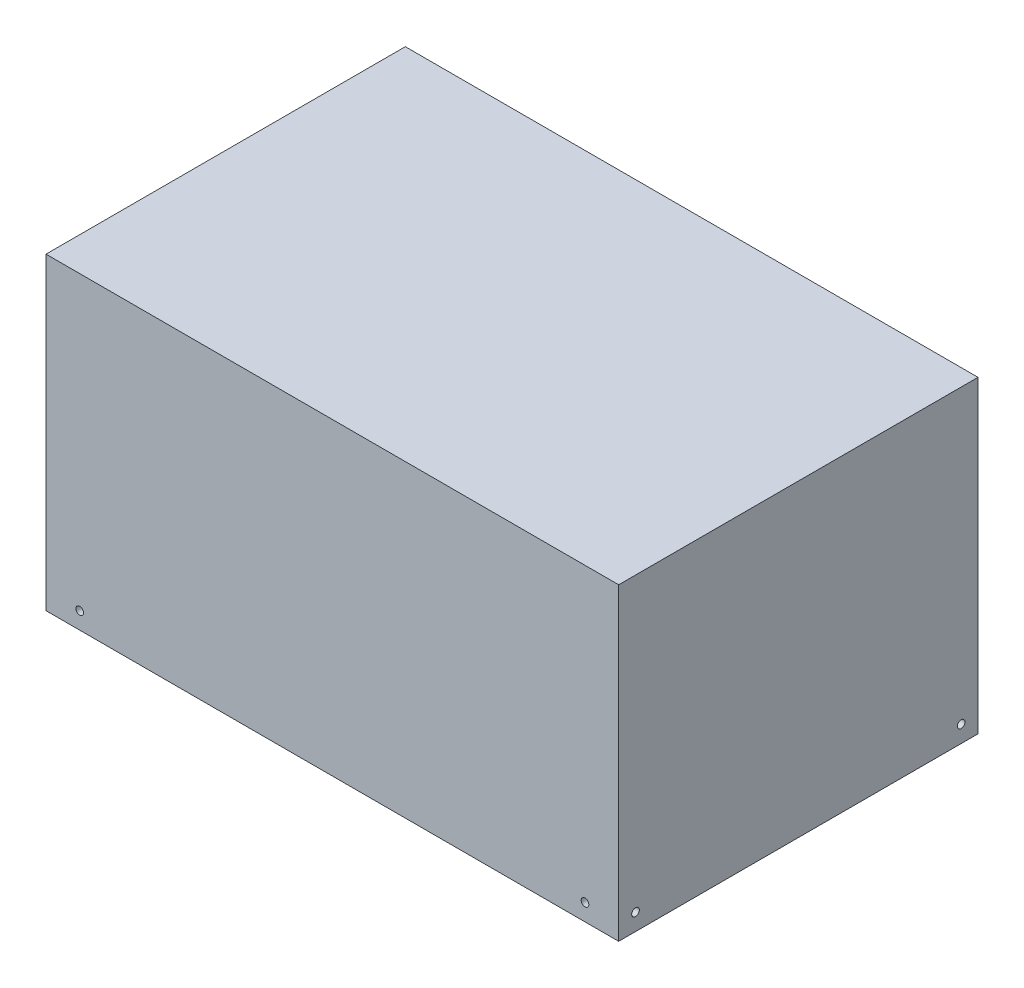
SolidWorks part; units mm, degrees
material "Acciaio al carbonio semplice"
ref_plane "Piano frontale" through (0, 0, 0) normal (0, 0, 1) x (1, 0, 0)
ref_plane "Piano superiore" through (0, 0, 0) normal (0, 1, 0) x (1, 0, 0)
ref_plane "Piano destro" through (0, 0, 0) normal (1, 0, 0) x (0, 0, -1)
sketch "Schizzo1" plane through (0, 0, 0) normal (0, 0, 1) x (1, 0, 0)
  line L1 (-255, 137.5) -> (255, 137.5)
  line L2 (-255, 137.5) -> (-255, -137.5)
  line L3 (-255, -137.5) -> (255, -137.5)
  line L4 (255, 137.5) -> (255, -137.5)
  line L5 (-255, 137.5) -> (255, -137.5) construction
  line L6 (-255, -137.5) -> (255, 137.5) construction
  point P0 (0, 0)
  dimension "D1" = 275
  dimension "D2" = 510
extrude "Estrusione-Estrusione1" add sketch "Schizzo1" along normal mid plane 320
hole_wizard "Foro filettato M8-1" positions "Schizzo2" profile "Schizzo4" tap size "M8" standard "ISO"
sketch "Schizzo2" plane through (0, 0, 160) normal (0, 0, 1) x (1, 0, 0)
  line L0 (-255, 137.5) -> (-255, -137.5) construction
  line L1 (-255, -137.5) -> (255, -137.5) construction
  line L3 (255, -137.5) -> (255, 137.5) construction
  point P0 (225, -122.5)
  point P2 (-225, -122.5)
  dimension "D1" = 30
  dimension "D2" = 15
  dimension "D3" = 15
  dimension "D4" = 30
sketch "Schizzo4" plane through (225, -122.5, 160) normal (1, 0, 0) x (0, -1, 0)
  line L0 (0, 0) -> (0, 10.2929)
  line L1 (0, 10.2929) -> (3.4, 8.25)
  line L2 (3.4, 8.25) -> (3.4, 0)
  line L5 (3.4, 0) -> (0, 0)
  line L10 (0, 10.2929) -> (-3.4, 8.25) construction
  line L11 (0, -6.35) -> (0, 107.95) construction
  dimension "Tap Drill Dia." = 6.8
  dimension "Tap Drill Depth" = 8.25
  dimension "Drill Angle" = 118
cosmetic thread "Filettatura del foro1"
cosmetic thread "Filettatura del foro2"
hole_wizard "Foro filettato M8-2" positions "Schizzo5" profile "Schizzo6" tap size "M8" standard "ISO"
sketch "Schizzo5" plane through (255, 0, 0) normal (1, 0, 0) x (0, 0, -1)
  line L0 (-160, -137.5) -> (-160, 137.5) construction
  line L1 (-160, -137.5) -> (160, -137.5) construction
  line L2 (160, -137.5) -> (160, 137.5) construction
  point P0 (-145, -122.5)
  point P2 (145, -122.5)
  dimension "D1" = 15
  dimension "D2" = 15
  dimension "D3" = 15
  dimension "D4" = 15
sketch "Schizzo6" plane through (255, -122.5, 145) normal (0, 1, 0) x (0, 0, -1)
  line L0 (0, 0) -> (0, 10.2929)
  line L1 (0, 10.2929) -> (3.4, 8.25)
  line L2 (3.4, 8.25) -> (3.4, 0)
  line L5 (3.4, 0) -> (0, 0)
  line L10 (0, 10.2929) -> (-3.4, 8.25) construction
  line L11 (0, -6.35) -> (0, 107.95) construction
  dimension "Tap Drill Dia." = 6.8
  dimension "Tap Drill Depth" = 8.25
  dimension "Drill Angle" = 118
cosmetic thread "Filettatura del foro3"
cosmetic thread "Filettatura del foro4"
mirror "Specchia1" about plane through (0, 0, 0) normal (0, 0, 1) of "Foro filettato M8-1"
cosmetic thread "Filettatura del foro5"
cosmetic thread "Filettatura del foro6"
